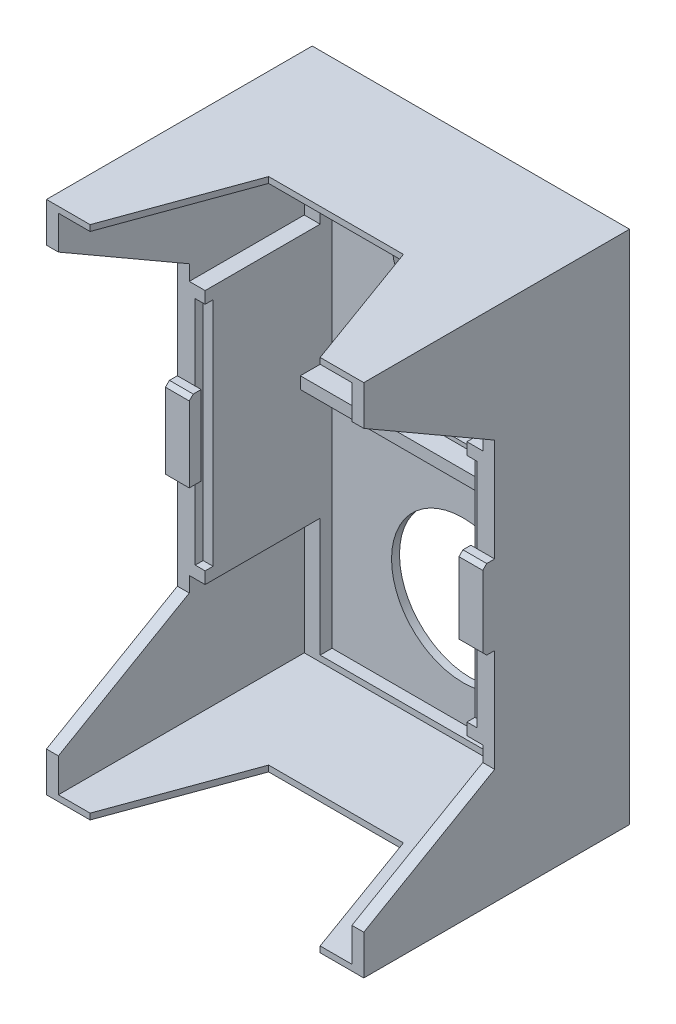
SolidWorks part; units mm, degrees
ref_plane "Front Plane" through (0, 0, 0) normal (1, 0, 0) x (0, 1, 0)
ref_plane "Top Plane" through (0, 0, 0) normal (0, 0, 1) x (0, 1, 0)
ref_plane "Right Plane" through (0, 0, 0) normal (0, 1, 0) x (-1, 0, 0)
sketch "Sketch1" plane through (0, 0, 0) normal (0, 0, 1) x (0, 1, 0)
  line L0 (-65, 0) -> (65, 0) construction
  line L1 (-65, -40) -> (65, -40)
  line L2 (-65, -40) -> (-65, 40)
  line L3 (-65, 40) -> (65, 40)
  line L4 (65, -40) -> (65, 40)
  line L5 (-65, -40) -> (65, 40) construction
  line L6 (-65, 40) -> (65, -40) construction
  line L7 (0, 40) -> (0, -40) construction
  circle A0 centre (-35, 0) radius 18
  circle A1 centre (35, 0) radius 18
  point P0 (0, 0)
  dimension "D3" = 36
  dimension "D4" = 30
  dimension "D1" = 80
  dimension "D2" = 130
extrude "Boss-Extrude1" add sketch "Sketch1" along normal blind 2
sketch "Sketch2" plane through (0, 0, 2) normal (0, 0, 1) x (1, 0, 0)
  line L0 (0, 65) -> (0, 0) construction
  line L1 (40, 65) -> (-40, 65) construction
  line L2 (-40, -65) -> (40, -65) construction
  line L3 (-35, -28.6) -> (35, -28.6) construction
  line L4 (-35, -28.6) -> (-35, 28.6) construction
  line L5 (-35, 28.6) -> (35, 28.6) construction
  line L6 (35, -28.6) -> (35, 28.6) construction
  line L7 (-35, -28.6) -> (35, 28.6) construction
  line L8 (-35, 28.6) -> (35, -28.6) construction
  line L9 (40, -65) -> (40, 65) construction
  line L10 (-40, 65) -> (-40, -65) construction
  line L11 (-40, -65) -> (-33, -65)
  line L12 (40, -65) -> (40, 65)
  line L13 (-40, 65) -> (-40, -65)
  line L14 (40, 65) -> (33, 65)
  line L15 (-33, -65) -> (-33, 65)
  line L16 (33, -65) -> (33, 65)
  line L17 (-33, -28.6) -> (-33, 28.6) construction
  line L18 (33, -28.6) -> (33, 28.6) construction
  line L19 (-33, 65) -> (-40, 65)
  line L20 (33, -65) -> (40, -65)
  point P5 (0, 0)
  dimension "D1" = 70
  dimension "D2" = 57.2
  dimension "D3" = 2
  dimension "D4" = 2
extrude "Boss-Extrude2" add sketch "Sketch2" along normal blind 30
sketch "Sketch3" plane through (0, 0, 32) normal (0, 0, 1) x (1, 0, 0)
  line L1 (-35, -28.6) -> (35, -28.6) construction
  line L2 (-35, -28.6) -> (-35, 28.6) construction
  line L3 (-35, 28.6) -> (35, 28.6) construction
  line L4 (35, -28.6) -> (35, 28.6) construction
  line L5 (-35, -28.6) -> (35, 28.6) construction
  line L6 (-35, 28.6) -> (35, -28.6) construction
  point P0 (0, 0)
  dimension "D1" = 70
  dimension "D2" = 57.2
sketch "Sketch4" plane through (0, 0, 32) normal (0, 0, 1) x (1, 0, 0)
  line L10 (-33, 29.1) -> (-35.5, 29.1)
  line L11 (-40, 65) -> (-33, 65)
  line L12 (-40, 65) -> (-40, -65)
  line L13 (-40, -65) -> (-33, -65)
  line L14 (-35.5, -29.1) -> (35.5, -29.1)
  line L15 (35.5, -29.1) -> (35.5, 29.1)
  line L16 (35.5, 29.1) -> (-35.5, 29.1)
  line L17 (-35.5, 29.1) -> (-35.5, -29.1)
  line L18 (-35.5, -29.1) -> (-33, -29.1)
  line L19 (35.5, -29.1) -> (35.5, 29.1)
  line L20 (35.5, 29.1) -> (33, 29.1)
  line L21 (-35.5, 29.1) -> (-35.5, -29.1)
  line L22 (-33, 65) -> (-33, 29.1)
  line L23 (40, -65) -> (33, -65)
  line L24 (40, -65) -> (40, 65)
  line L25 (40, 65) -> (33, 65)
  line L26 (33, -65) -> (33, -29.1)
  line L27 (-33, -29.1) -> (-33, -65)
  line L28 (33, -29.1) -> (35.5, -29.1)
  line L29 (33, 29.1) -> (33, 65)
  dimension "D1" = 0.5
extrude "Boss-Extrude3" add sketch "Sketch4" along normal blind 35
sketch "Sketch5" plane through (0, 0, 67) normal (0, 0, 1) x (1, 0, 0)
  line L1 (-75, -55) -> (75, -55)
  line L2 (-75, -55) -> (-75, 55)
  line L3 (-75, 55) -> (75, 55)
  line L4 (75, -55) -> (75, 55)
  line L5 (-75, -55) -> (75, 55) construction
  line L6 (-75, 55) -> (75, -55) construction
  point P0 (0, 0)
  dimension "D1" = 110
  dimension "D2" = 150
extrude "Cut-Extrude1" cut sketch "Sketch5" against normal offset from surface 2 draft 30 up to face at (-34.25, 0, 32)
sketch "Sketch6" plane through (0, 0, 34) normal (0, 0, 1) x (1, 0, 0)
  line L0 (0, 0) -> (75.8443, 0) construction
  line L1 (40, -35.9474) -> (40, 35.9474) construction
  line L2 (40, 10) -> (34, 10)
  line L3 (40, 10) -> (40, -10)
  line L4 (40, -10) -> (34, -10)
  line L5 (34, 10) -> (34, -10)
  line L6 (35.5, 29.1) -> (35.5, -29.1) construction
  line L7 (0, 0) -> (0, 28.6) construction
  line L8 (-35, 28.6) -> (35, 28.6) construction
  line L9 (-40, -10) -> (-34, -10)
  line L10 (-34, 10) -> (-34, -10)
  line L11 (-40, 10) -> (-40, -10)
  line L12 (-40, 10) -> (-34, 10)
  dimension "D1" = 10
  dimension "D2" = 10
  dimension "D3" = 1.5
extrude "Boss-Extrude4" add sketch "Sketch6" along normal blind 3
chamfer "Chamfer1" distance 1 angle 45 3 edges at (-37, 10, 37) (37, -10, 37) (37, 10, 37)
sketch "Sketch7" plane through (0, 0, 2) normal (0, 0, 1) x (1, 0, 0)
  line L0 (40, -9) -> (40, 9) construction
  line L1 (-40, -2.5) -> (40, -2.5)
  line L2 (-40, -2.5) -> (-40, 2.5)
  line L3 (-40, 2.5) -> (40, 2.5)
  line L4 (40, -2.5) -> (40, 2.5)
  line L5 (-40, -2.5) -> (40, 2.5) construction
  line L6 (-40, 2.5) -> (40, -2.5) construction
  line L12 (40, -65) -> (40, -55) construction
  line L13 (-40, -65) -> (40, -65)
  line L14 (-40, -65) -> (-40, -62)
  line L15 (-40, -62) -> (40, -62)
  line L16 (40, -65) -> (40, -62)
  line L17 (40, 55) -> (40, 65) construction
  line L18 (-40, 65) -> (40, 65)
  line L19 (-40, 65) -> (-40, 62)
  line L20 (-40, 62) -> (40, 62)
  line L21 (40, 65) -> (40, 62)
  point P0 (0, 0)
  dimension "D1" = 5
  dimension "D2" = 3
  dimension "D3" = 3
extrude "Boss-Extrude5" add sketch "Sketch7" along normal blind 3
sketch "Sketch9" plane through (0, 0, 5) normal (0, 0, 1) x (1, 0, 0)
  line L0 (-33, 65) -> (-40, 65) construction
  line L1 (-37, 65) -> (37, 65)
  line L2 (-37, 65) -> (-37, 32.1)
  line L3 (-37, 32.1) -> (37, 32.1)
  line L4 (37, 65) -> (37, 32.1)
  line L5 (-40, 65) -> (-40, 55) construction
  line L6 (-35.5, 29.1) -> (-33, 29.1) construction
  line L7 (40, 55) -> (40, 65) construction
  line L8 (0, 0) -> (111.8745, 0) construction
  line L9 (-37, -65) -> (-37, -32.1)
  line L10 (-37, -32.1) -> (37, -32.1)
  line L11 (37, -65) -> (37, -32.1)
  line L12 (-37, -65) -> (37, -65)
  dimension "D1" = 3
  dimension "D2" = 3
  dimension "D3" = 3
extrude "Cut-Extrude2" cut sketch "Sketch9" along normal through all contours L2 L1 L4 L3 | L9 L10 L11 L12
sketch "Sketch10" plane through (0, 0, 5) normal (0, 0, 1) x (1, 0, 0)
  line L1 (-36.2026, 1.5) -> (36.2026, 1.5)
  line L2 (-36.2026, 1.5) -> (-36.2026, -1.5)
  line L3 (-36.2026, -1.5) -> (36.2026, -1.5)
  line L4 (36.2026, 1.5) -> (36.2026, -1.5)
  line L5 (-36.2026, 1.5) -> (36.2026, -1.5) construction
  line L6 (-36.2026, -1.5) -> (36.2026, 1.5) construction
  point P0 (0, 0)
  dimension "D1" = 3
extrude "Boss-Extrude6" add sketch "Sketch10" along normal blind 5
sketch "Sketch11" plane through (0, 0, 5) normal (0, 0, 1) x (1, 0, 0)
  line L0 (-40, 65) -> (-40, 55) construction
  line L1 (-40, 65) -> (40, 65)
  line L2 (-40, 65) -> (-40, 63.5)
  line L3 (-40, 63.5) -> (40, 63.5)
  line L4 (40, 65) -> (40, 63.5)
  line L5 (-37, 65) -> (-40, 65) construction
  line L6 (40, 55) -> (40, 65) construction
  line L7 (40, -65) -> (40, -55) construction
  line L8 (-40, -65) -> (40, -65)
  line L9 (-40, -65) -> (-40, -63.5)
  line L10 (-40, -63.5) -> (40, -63.5)
  line L11 (40, -65) -> (40, -63.5)
  dimension "D1" = 1.5
  dimension "D2" = 1.5
extrude "Boss-Extrude7" add sketch "Sketch11" along normal up to surface (62 mm away) up to face at (38.5, 60, 67)
sketch "Sketch12" plane through (0, 0, 67) normal (0, 0, 1) x (1, 0, 0)
  line L0 (0, 90.3771) -> (0, -100.3421) construction
  line L1 (-37, 63.5) -> (37, 63.5) construction
  line L2 (-29, 49.0817) -> (29, 49.0817)
  line L3 (-29, 49.0817) -> (-29, 77.9183)
  line L4 (-29, 77.9183) -> (29, 77.9183)
  line L5 (29, 49.0817) -> (29, 77.9183)
  line L6 (-29, 49.0817) -> (29, 77.9183) construction
  line L7 (-29, 77.9183) -> (29, 49.0817) construction
  line L8 (-37, 63.5) -> (-37, 32.1) construction
  line L9 (0, 0) -> (85.4272, 0) construction
  line L10 (-29, -49.0817) -> (-29, -77.9183)
  line L11 (-29, -49.0817) -> (29, -49.0817)
  line L12 (29, -49.0817) -> (29, -77.9183)
  line L13 (-29, -77.9183) -> (29, -77.9183)
  point P3 (0, 63.5)
  dimension "D1" = 8
extrude "Cut-Extrude3" cut sketch "Sketch12" against normal up to surface (33 mm away) draft 20
